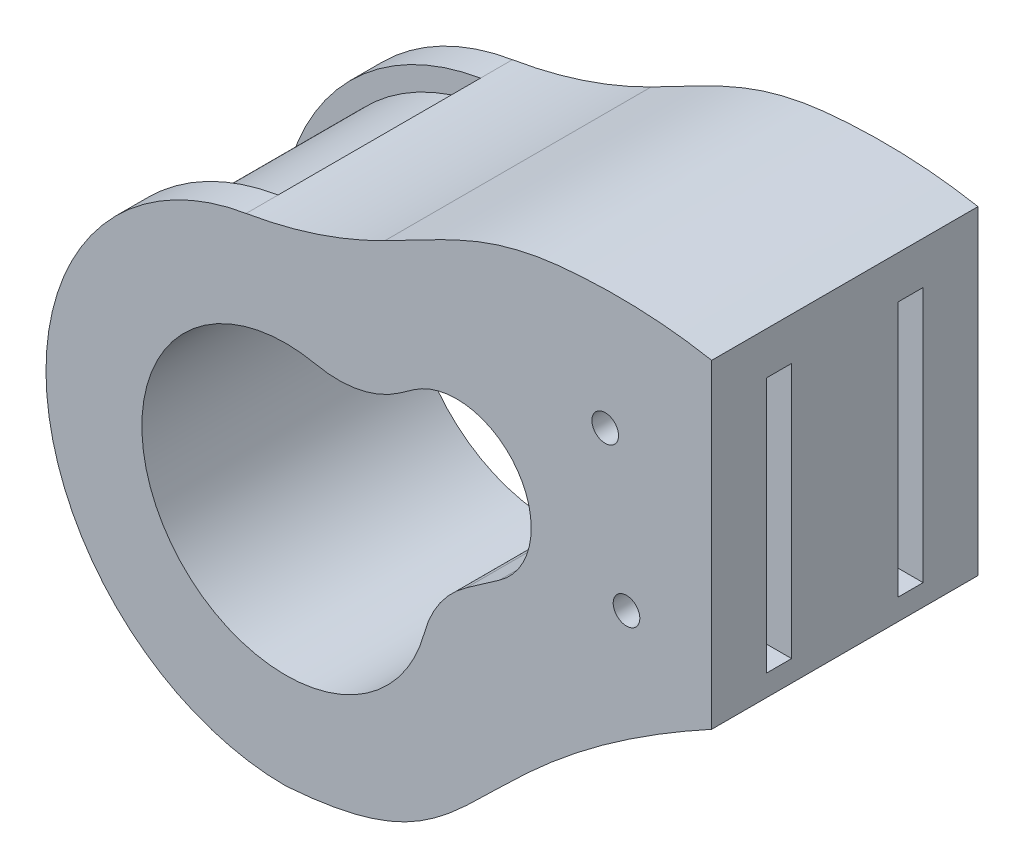
SolidWorks part; units mm, degrees
ref_plane "Front Plane" through (0, 0, 0) normal (0, 0, 1) x (1, 0, 0)
ref_plane "Top Plane" through (0, 0, 0) normal (0, 1, 0) x (1, 0, 0)
ref_plane "Right Plane" through (0, 0, 0) normal (1, 0, 0) x (0, 0, -1)
sketch "Sketch1" plane through (0, 0, 0) normal (0, 0, 1) x (1, 0, 0)
  line L1 (40, 2.1018) -> (40, 32.1018)
  arc A5 (-3.7081, 22.1923) -> (0, -22.5) centre (0, 0) ccw
  arc A8 (9.3108, 26.4845) -> (-3.7081, 22.1923) centre (-11.1243, 66.577) cw
  spline S0 degree 3 poles (40, 32.1018) (34.3298, 33.1632) (26.9825, 32.8408) (18.5729, 31.6534) (14.8593, 29.3126) (9.3108, 26.4845) knots 0 0 0 0 0.184099 0.26818 0.840804 0.840804 0.840804 0.840804
  spline S2 degree 3 poles (40, 2.1018) (14.754, -11.6921) (19.3202, -21.0911) (0, -22.5) knots 0 0 0 0 1 1 1 1
  dimension "D1" = 45
  dimension "D4" = 45
  dimension "D3" = 40
  dimension "D2" = 30
extrude "Boss-Extrude1" add sketch "Sketch1" along normal blind 25
sketch "Sketch2" plane through (40, 0, 0) normal (1, 0, 0) x (0, 0, -1)
  line L1 (-17.5, 28.1018) -> (-19.85, 28.1018)
  line L2 (-17.5, 28.1018) -> (-17.5, 4.1018)
  line L3 (-17.5, 4.1018) -> (-19.85, 4.1018)
  line L4 (-19.85, 28.1018) -> (-19.85, 4.1018)
  line L5 (-17.5, 28.1018) -> (-19.85, 4.1018) construction
  line L6 (-17.5, 4.1018) -> (-19.85, 28.1018) construction
  line L7 (-25, 2.1018) -> (0, 2.1018) construction
  line L8 (-12.5, 2.1018) -> (-12.5, -3.8471) construction
  line L9 (-7.5, 4.1018) -> (-5.15, 4.1018)
  line L10 (-5.15, 28.1018) -> (-5.15, 4.1018)
  line L11 (-7.5, 28.1018) -> (-5.15, 28.1018)
  line L12 (-7.5, 28.1018) -> (-7.5, 4.1018)
  point P6 (-12.5, 2.1018)
  dimension "D1" = 2.35
  dimension "D2" = 24
  dimension "D3" = 5
  dimension "D4" = 2
extrude "Cut-Extrude1" cut sketch "Sketch2" against normal blind 23
sketch "Sketch3" plane through (0, 0, 25) normal (0, 0, 1) x (1, 0, 0)
  line L0 (30, 21.6018) -> (32, 7.7454) construction
  line L1 (30, 9.6018) -> (30, 21.6018) construction
  line L2 (40, 2.1018) -> (40, 32.1018) construction
  circle A1 centre (30, 21.6018) radius 1.25
  circle A3 centre (32, 7.7454) radius 1.25
  point P7 (30, 15.6018)
  dimension "D1" = 2.5
  dimension "D2" = 2.5
  dimension "D4" = 6.5
  dimension "D5" = 10
  dimension "D7" = 8
  dimension "D3" = 12
  dimension "D6" = 14
extrude "Cut-Extrude2" cut sketch "Sketch3" against normal through all
sketch "Sketch4" plane through (0, 0, 25) normal (0, 0, 1) x (1, 0, 0)
  line L0 (12.7745, 7.7067) -> (16.0533, 9.9979) construction
  line L1 (10.6718, 14.7771) -> (12.0438, 15.7358)
  line L2 (16.9663, 2.0961) -> (20.0629, 4.26)
  arc A1 (2.8401, 13.1979) -> (13.0371, -3.5047) centre (0, 0) ccw
  arc A3 (20.0629, 4.26) -> (12.0438, 15.7358) centre (16.0533, 9.9979) ccw
  arc A4 (10.6718, 14.7771) -> (2.8401, 13.1979) centre (4.9439, 22.9741) cw
  arc A5 (16.9663, 2.0961) -> (13.0371, -3.5047) centre (22.6943, -6.1009) ccw
  point P5 (7.7403, 5.4088)
  dimension "D1" = 27
  dimension "D2" = 14
extrude "Cut-Extrude3" cut sketch "Sketch4" against normal through all
fillet "Fillet4" [suppressed] radius 3
ref_plane "Plane1" through (0, -22.5, 12.5) normal (0, -1, 0) x (-1, 0, 0)
sketch "Sketch5" [suppressed] plane through (0, -22.5, 12.5) normal (0, -1, 0) x (-1, 0, 0)
  line L0 (14.5001, 12.5) -> (-14.2627, 12.5) construction
  circle A0 centre (1.8077, 0) radius 1
  dimension "D1" = 2
  dimension "D2" = 12.5
extrude "Cut-Extrude4" [suppressed] cut sketch "Sketch5" against normal up to next
sketch "Sketch6" plane through (0, 0, 25) normal (0, 0, 1) x (1, 0, 0)
  line L1 (40, 2.1018) -> (40, 32.1018)
  line L3 (-3.7081, 22.1923) -> (-3.3785, 20.2197)
  line L4 (17.5335, -12.2922) -> (18.9331, -13.7208)
  arc A2 (-3.7081, 22.1923) -> (9.3108, 26.4845) centre (-11.1243, 66.577) ccw
  arc A3 (-3.7081, 22.1923) -> (0, -22.5) centre (0, 0) ccw
  arc A5 (-3.7081, 22.1923) -> (0, -22.5) centre (0, 0) ccw
  arc A7 (-3.3785, 20.2197) -> (-0.0718, -20.4999) centre (0, 0) ccw
  spline S2 degree 3 poles (-465.3978, -830.7758) (247.9389, 35.0033) (41.3936, 34.8756) (-12.3549, 27.2864) (43.1789, -24.0671) (-988.278, -42.8876) knots -1.440841 -1.440841 -1.440841 -1.440841 0.184099 0.26818 3.933011 3.933011 3.933011 3.933011 only from (40, 32.1018) to (9.3108, 26.4845)
  spline S3 degree 3 poles (-990.4917, 115.0715) (936.4798, -142.8698) (-907.1023, 24.5078) (1034.0108, 111.3833) knots -2.150862 -2.150862 -2.150862 -2.150862 3.050243 3.050243 3.050243 3.050243 only from (0, -22.5) to (40, 2.1018)
  spline S5 degree 3 poles (0, -22.5) (10.4852, -21.7354) (13.9351, -18.6174) (18.9331, -13.7208) knots 0 0 0 0 0.542706 0.542706 0.542706 0.542706
  spline S7 degree 3 poles (-0.0718, -20.4999) (0.2086, -20.4791) (0.7771, -20.4324) (1.8473, -20.3265) (3.1084, -20.1677) (4.4942, -19.9375) (6.1897, -19.5795) (8.0471, -19.0406) (9.9483, -18.2572) (11.6226, -17.335) (13.6847, -15.9016) (15.4423, -14.3236) (16.9494, -12.8637) (17.3925, -12.4303) (17.5335, -12.2922) knots 0.001319 0.001319 0.001319 0.001319 0.016709 0.032099 0.062878 0.093658 0.124437 0.185997 0.247556 0.309115 0.370674 0.493792 0.527316 0.542706 0.542706 0.542706 0.542706
  dimension "D1" = 0
extrude "Cut-Extrude5" cut sketch "Sketch6" against normal blind 19 from offset 3 offset against normal yes
ref_plane "Plane2" through (-3.3785, 20.2197, 0) normal (-0.1648, 0.9863, 0) x (0.9863, 0.1648, 0)
sketch "Sketch9" plane through (-3.3785, 20.2197, 0) normal (-0.1648, 0.9863, 0) x (0.9863, 0.1648, 0)
  line L0 (0, -3) -> (0, -22) construction
  line L1 (0, -6) -> (-2.7, -6)
  line L2 (0, -6) -> (0, -19)
  line L3 (0, -19) -> (-2.7, -19)
  line L4 (-2.7, -6) -> (-2.7, -19)
  line L5 (-20.5, -3) -> (0, -3) construction
  line L6 (0, -22) -> (-22.5, -22) construction
  dimension "D1" = 3
  dimension "D2" = 3
  dimension "D3" = 2.7
extrude "Cut-Extrude6" cut sketch "Sketch9" against normal up to next
ref_plane "Plane3" through (14.3463, -14.6435, 0) normal (0.6998, -0.7143, 0) x (-0.7143, -0.6998, 0)
sketch "Sketch10" plane through (14.3463, -14.6435, 0) normal (0.6998, -0.7143, 0) x (-0.7143, -0.6998, 0)
  line L0 (-3.9222, -3) -> (-3.9222, -22) construction
  line L1 (-3.9222, -6) -> (-1.2222, -6)
  line L2 (-3.9222, -6) -> (-3.9222, -19)
  line L3 (-3.9222, -19) -> (-1.2222, -19)
  line L4 (-1.2222, -6) -> (-1.2222, -19)
  line L5 (-3.9222, -3) -> (15.746, -3) construction
  line L6 (15.746, -22) -> (-3.9222, -22) construction
  dimension "D1" = 3
  dimension "D2" = 3
  dimension "D3" = 2.7
extrude "Cut-Extrude7" cut sketch "Sketch10" against normal up to next and the other way up to next
sketch "Sketch13" plane through (0, 0, 0) normal (0, 0, -1) x (-1, 0, 0)
  line L0 (-40, 2.1018) -> (-40, 32.1018) construction
  line L1 (-27.75, 20.3028) -> (-27.75, 22.9008)
  line L2 (-27.75, 22.9008) -> (-30, 24.1999)
  line L3 (-30, 24.1999) -> (-32.25, 22.9008)
  line L4 (-32.25, 22.9008) -> (-32.25, 20.3028)
  line L5 (-32.25, 20.3028) -> (-30, 19.0037)
  line L6 (-30, 19.0037) -> (-27.75, 20.3028)
  line L7 (-29.75, 9.0444) -> (-32, 10.3435)
  line L8 (-32, 10.3435) -> (-34.25, 9.0444)
  line L9 (-34.25, 9.0444) -> (-34.25, 6.4464)
  line L10 (-34.25, 6.4464) -> (-32, 5.1473)
  line L11 (-32, 5.1473) -> (-29.75, 6.4464)
  line L12 (-29.75, 6.4464) -> (-29.75, 9.0444)
  circle A0 centre (-30, 21.6018) radius 2.25 construction
  circle A1 centre (-32, 7.7454) radius 2.25 construction
  point P20 (0, 0)
  dimension "D1" = 4.5
extrude "Cut-Extrude8" cut sketch "Sketch13" against normal blind 1.5
